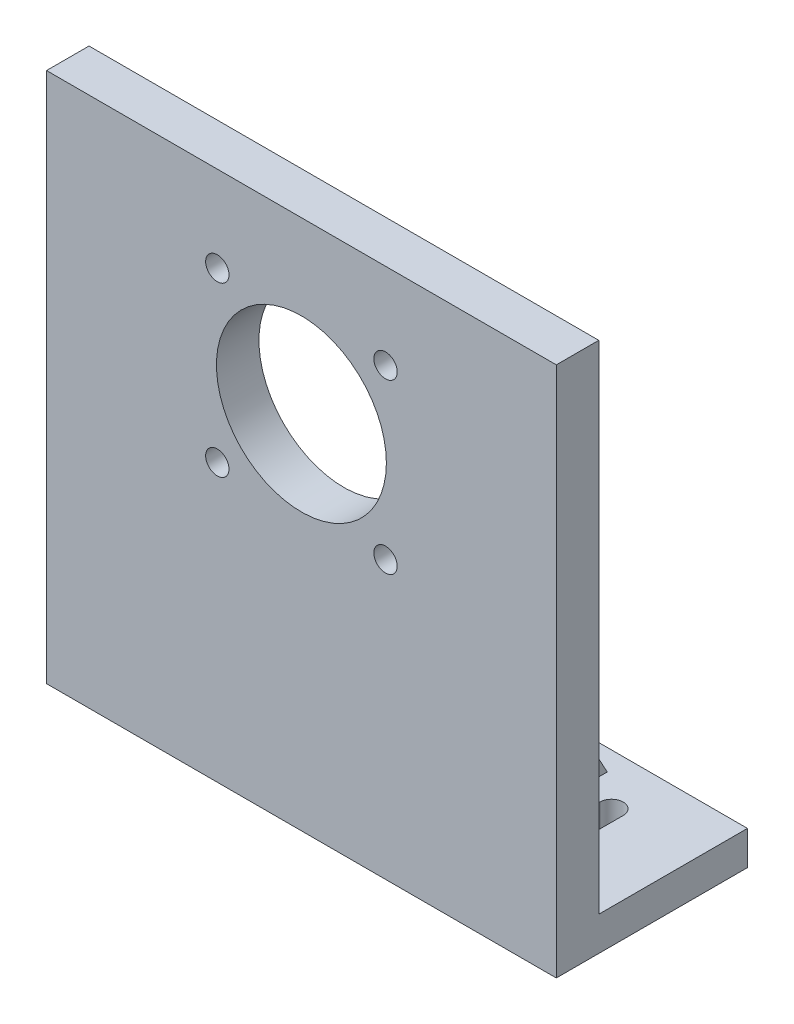
SolidWorks part; units mm, degrees
ref_plane "前视基准面" through (0, 0, 0) normal (0, 0, 1) x (1, 0, 0)
ref_plane "上视基准面" through (0, 0, 0) normal (0, 1, 0) x (1, 0, 0)
ref_plane "右视基准面" through (0, 0, 0) normal (1, 0, 0) x (0, 0, -1)
other "Configuration Table"
sketch "草图1" plane through (0, 0, 0) normal (0, 0, 1) x (1, 0, 0)
  line L1 (-60, 0) -> (60, 0)
  line L2 (-60, 0) -> (-60, 125)
  line L3 (-60, 125) -> (60, 125)
  line L4 (60, 0) -> (60, 125)
  circle A0 centre (0, 85) radius 20
  circle A1 centre (19.799, 104.799) radius 2.75
  circle A2 centre (-19.799, 104.799) radius 2.75
  circle A3 centre (-19.799, 65.201) radius 2.75
  circle A4 centre (19.799, 65.201) radius 2.75
extrude "凸台-拉伸1" add sketch "草图1" against normal blind 10
sketch "草图2" plane through (0, 0, 0) normal (0, 1, 0) x (1, 0, 0)
  line L0 (-40, 27.5) -> (-40, 33) construction
  line L1 (-60, 10) -> (60, 10)
  line L2 (-60, 10) -> (-60, 45)
  line L3 (-60, 45) -> (60, 45)
  line L4 (60, 10) -> (60, 45)
  line L5 (-42.75, 27.5) -> (-42.75, 33)
  line L6 (-37.25, 27.5) -> (-37.25, 33)
  line L7 (40, 27.5) -> (40, 33) construction
  line L8 (37.25, 27.5) -> (37.25, 33)
  line L9 (42.75, 27.5) -> (42.75, 33)
  arc A0 (-42.75, 27.5) -> (-37.25, 27.5) centre (-40, 27.5) ccw
  arc A1 (-37.25, 33) -> (-42.75, 33) centre (-40, 33) ccw
  arc A2 (37.25, 27.5) -> (42.75, 27.5) centre (40, 27.5) ccw
  arc A3 (42.75, 33) -> (37.25, 33) centre (40, 33) ccw
  point P7 (-40, 30.25)
  point P12 (40, 30.25)
extrude "凸台-拉伸3" add sketch "草图2" along normal blind 8
sketch "草图3" plane through (0, 0, 0) normal (1, 0, 0) x (0, 0, -1)
  line L0 (10, 8) -> (40, 8)
  line L1 (40, 8) -> (10, 63)
  line L2 (10, 63) -> (10, 8)
extrude "凸台-拉伸4" add sketch "草图3" against normal mid plane 64
sketch "草图4" plane through (0, 0, 0) normal (1, 0, 0) x (0, 0, -1)
  line L0 (10, 8) -> (40, 8)
  line L1 (40, 8) -> (10, 63)
  line L2 (10, 63) -> (10, 8)
extrude "切除-拉伸1" cut sketch "草图4" against normal mid plane 48
